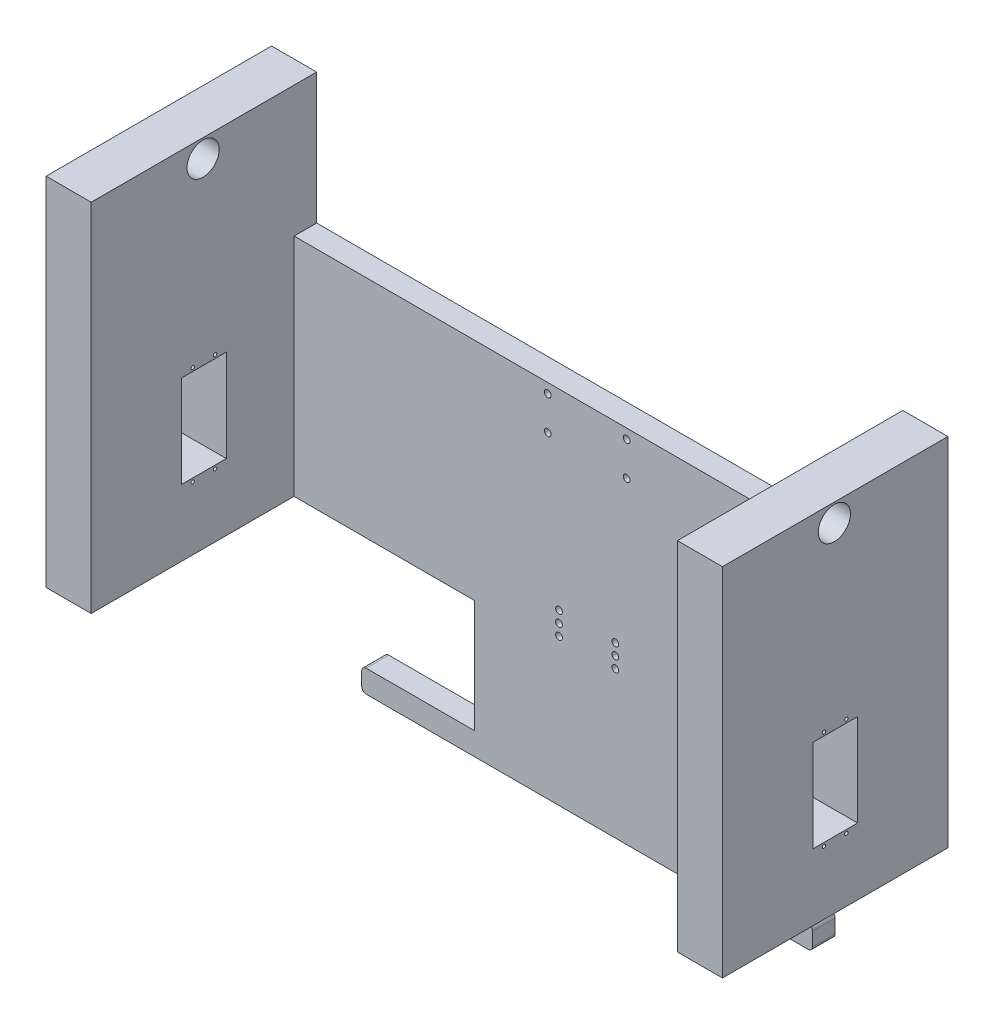
SolidWorks part; units mm, degrees
ref_plane "Front Plane" through (0, 0, 0) normal (0, 0, 1) x (1, 0, 0)
ref_plane "Top Plane" through (0, 0, 0) normal (0, 1, 0) x (1, 0, 0)
ref_plane "Right Plane" through (0, 0, 0) normal (1, 0, 0) x (0, 0, -1)
sketch "Sketch1" plane through (0, 0, 0) normal (0, 0, 1) x (1, 0, 0)
  line L1 (-150, 50) -> (150, 50)
  line L2 (-150, 50) -> (-150, -50)
  line L3 (-150, -50) -> (150, -50)
  line L4 (150, 50) -> (150, -50)
  line L5 (-150, 50) -> (150, -50) construction
  line L6 (-150, -50) -> (150, 50) construction
  point P0 (0, 0)
  dimension "D1" = 300
  dimension "D2" = 100
extrude "Boss-Extrude1" add sketch "Sketch1" along normal blind 10
sketch "Sketch2" plane through (0, 0, 10) normal (0, 0, 1) x (1, 0, 0)
  line L0 (-150, -50) -> (150, -50) construction
  line L1 (-150, 50) -> (-130, 50)
  line L2 (-150, 50) -> (-150, -50)
  line L3 (-150, -50) -> (-130, -50)
  line L4 (-130, 50) -> (-130, -50)
  line L6 (150, 50) -> (130, 50)
  line L7 (150, 50) -> (150, -50)
  line L8 (150, -50) -> (130, -50)
  line L9 (130, 50) -> (130, -50)
  dimension "D1" = 20
extrude "Boss-Extrude2" add sketch "Sketch2" along normal blind 90
sketch "Sketch3" plane through (-150, 0, 0) normal (-1, 0, 0) x (0, 0, 1)
  line L0 (0, 50) -> (100, -50) construction
  line L1 (50, 50) -> (50, -50) construction
  line L2 (40.05, 20.45) -> (59.95, 20.45)
  line L3 (40.05, 20.45) -> (40.05, -20.45)
  line L4 (40.05, -20.45) -> (59.95, -20.45)
  line L5 (59.95, 20.45) -> (59.95, -20.45)
  line L6 (40.05, 20.45) -> (59.95, -20.45) construction
  line L7 (40.05, -20.45) -> (59.95, 20.45) construction
  line L8 (100, 50) -> (0, 50) construction
  line L9 (100, -50) -> (0, -50) construction
  line L10 (40.639, 23.45) -> (59.361, 23.45)
  line L11 (40.05, -23.45) -> (59.95, -23.45)
  line L12 (40.05, 20.45) -> (50, 23.45) construction
  line L13 (50, 23.45) -> (59.95, 20.45) construction
  line L14 (40.05, -20.45) -> (50, -23.45) construction
  line L15 (50, -23.45) -> (59.95, -20.45) construction
  circle A0 centre (45.025, 21.95) radius 0.75
  circle A1 centre (54.975, 21.95) radius 0.75
  circle A2 centre (45.025, -21.95) radius 0.75
  circle A3 centre (54.975, -21.95) radius 0.75
  point P4 (50, 0)
  point P18 (50, 23.45)
  point P21 (50, -23.45)
  dimension "D5" = 1.5
  dimension "D1" = 40.9
  dimension "D2" = 19.9
  dimension "D3" = 3
  dimension "D4" = 3
extrude "Cut-Extrude1" cut sketch "Sketch3" against normal through all contours L5 L2 L3 L4 | A0 | A1 | A2 | A3
sketch "Sketch4" plane through (0, -50, 0) normal (0, -1, 0) x (1, 0, 0)
  line L0 (150, 100) -> (150, 0) construction
  line L1 (-150, 0) -> (150, 0)
  line L2 (-150, 0) -> (-150, 10.0314)
  line L3 (-150, 10.0314) -> (150, 10.0314)
  line L4 (150, 0) -> (150, 10.0314)
  line L5 (-150, 0) -> (150, 10.0314) construction
  line L7 (-50, 10.0314) -> (50, 10.0314)
  line L8 (-50, 10.0314) -> (-50, 0)
  line L9 (-50, 0) -> (50, 0)
  line L10 (50, 10.0314) -> (50, 0)
  line L11 (-50, 10.0314) -> (50, 0) construction
  line L12 (-50, 0) -> (50, 10.0314) construction
  point P7 (0, 5.0157)
  line M5 (130, 10) -> (-130, 10)
  dimension "D1" = 100
extrude "Boss-Extrude4" add sketch "Sketch4" along normal blind 60 contours L10 L8 L1 M5
sketch "Sketch6" plane through (0, -110, 0) normal (0, -1, 0) x (1, 0, 0)
  line L0 (-50, 10) -> (50, 0) construction
  line L1 (50, 0) -> (150, 0) construction
  line L2 (-100, 10) -> (100, 10)
  line L3 (-100, 10) -> (-100, 0)
  line L4 (-100, 0) -> (100, 0)
  line L5 (100, 10) -> (100, 0)
  line L6 (-100, 10) -> (100, 0) construction
  line L7 (-100, 0) -> (100, 10) construction
  point P4 (0, 5)
  dimension "D1" = 200
extrude "Boss-Extrude5" add sketch "Sketch6" against normal blind 10
fillet "Fillet1" radius 2 4 edges at (100, -100, 5) (100, -110, 5) (-100, -110, 5) (-100, -100, 5)
sketch "Sketch8" plane through (0, 50, 0) normal (0, 1, 0) x (1, 0, 0)
  line L1 (-150, 0) -> (-130, 0)
  line L2 (-150, 0) -> (-150, -100)
  line L3 (-150, -100) -> (-130, -100)
  line L4 (-130, 0) -> (-130, -100)
  line L5 (130, -100) -> (150, -100)
  line L6 (130, -100) -> (130, 0)
  line L7 (130, 0) -> (150, 0)
  line L8 (150, -100) -> (150, 0)
extrude "Boss-Extrude7" add sketch "Sketch8" along normal blind 50
sketch "Sketch9" plane through (-150, 0, 0) normal (-1, 0, 0) x (0, 0, 1)
  line L1 (0, 100) -> (100, 100)
  line L2 (0, 100) -> (0, 108)
  line L3 (0, 108) -> (100, 108)
  line L4 (100, 100) -> (100, 108)
  line L5 (0, 100) -> (100, 100)
  line L6 (0, 100) -> (0, 102.5)
  line L7 (0, 102.5) -> (100, 102.5)
  line L8 (100, 100) -> (100, 102.5)
  circle A0 centre (50, 102.5) radius 1.5
  dimension "D4" = 3
  dimension "D1" = 100
  dimension "D2" = 8
  dimension "D3" = 2.5
extrude "Boss-Extrude9" add sketch "Sketch9" against normal through all
sketch "Sketch12" plane through (0, 100, 0) normal (0, -1, 0) x (1, 0, 0)
  line L1 (-130, 100) -> (130, 100)
  line L2 (-130, 100) -> (-130, 0)
  line L3 (-130, 0) -> (130, 0)
  line L4 (130, 100) -> (130, 0)
extrude "Cut-Extrude4" cut sketch "Sketch12" against normal blind 20
sketch "Sketch13" plane through (0, 0, 10) normal (0, 0, 1) x (1, 0, 0)
  line L0 (50, -50) -> (130, -50) construction
  line L1 (-25, 50) -> (25, 50)
  line L2 (-25, 50) -> (-25, -50)
  line L3 (-25, -50) -> (25, -50)
  line L4 (25, 50) -> (25, -50)
  line L5 (-25, 50) -> (25, -50) construction
  line L6 (-25, -50) -> (25, 50) construction
  line L7 (-25, -30) -> (25, -50) construction
  line L8 (-25, -50) -> (25, -50)
  line L9 (-25, -50) -> (-25, -30)
  line L10 (-25, -30) -> (25, -30)
  line L11 (25, -50) -> (25, -30)
  line L12 (-25, -40) -> (25, -40) construction
  line L13 (-25, -50) -> (25, -30) construction
  line L14 (0, -30) -> (0, -50) construction
  line L15 (0, -30) -> (-25, -40) construction
  line L16 (-25, -40) -> (0, -50) construction
  line L17 (0, -50) -> (25, -40) construction
  line L18 (25, -40) -> (0, -30) construction
  circle A0 centre (-12.5, -35) radius 1.5
  circle A1 centre (-12.5, -40) radius 1.5
  circle A2 centre (-12.5, -45) radius 1.5
  circle A3 centre (12.5, -45) radius 1.5
  circle A4 centre (12.5, -40) radius 1.5
  circle A5 centre (12.5, -35) radius 1.5
  point P0 (0, 0)
  dimension "D3" = 3
  dimension "D1" = 50
  dimension "D2" = 20
extrude "Cut-Extrude5" cut sketch "Sketch13" against normal through all contours A5 | A4 | A3 | A0 | A1 | A2
sketch "Sketch14" plane through (150, 0, 0) normal (1, 0, 0) x (0, 0, -1)
  line L0 (0, -50) -> (0, 108) construction
  line L1 (-100, 108) -> (0, 108)
  line L2 (-100, 108) -> (-100, 92)
  line L3 (-100, 92) -> (0, 92)
  line L4 (0, 108) -> (0, 92)
  line L5 (-100, 92) -> (0, 108)
  circle A0 centre (-50.3725, 99.9404) radius 7.15
  dimension "D2" = 14.3
  dimension "D1" = 16
extrude "Cut-Extrude7" cut sketch "Sketch14" against normal through all contours A0
sketch "Sketch15" plane through (0, 0, 0) normal (0, 0, -1) x (-1, 0, 0)
  line L0 (0, 0) -> (0, 50) construction
  line L1 (-130, 50) -> (130, 50)
  line L2 (-130, 50) -> (-130, 0)
  line L3 (-130, 0) -> (130, 0)
  line L4 (130, 50) -> (130, 0)
  line L5 (-17.5, 45.6804) -> (17.5, 45.6804) construction
  line L6 (0, 50) -> (-17.5, 50)
  line L7 (0, 50) -> (0, 25)
  line L8 (0, 25) -> (-17.5, 25)
  line L9 (-17.5, 50) -> (-17.5, 25)
  line L10 (0, 50) -> (17.5, 50)
  line L11 (0, 50) -> (0, 25)
  line L12 (0, 25) -> (17.5, 25)
  line L13 (17.5, 50) -> (17.5, 25)
  circle A0 centre (-17.5, 45.6804) radius 1.5
  circle A1 centre (17.5, 45.6804) radius 1.5
  circle A2 centre (-17.5, 30.6804) radius 1.5
  circle A3 centre (17.5, 30.7861) radius 1.5
  dimension "D3" = 3
  dimension "D1" = 35
  dimension "D2" = 25
  dimension "D4" = 15
extrude "Cut-Extrude8" cut sketch "Sketch15" against normal through all contours A1 | A3 | A2 | A0
